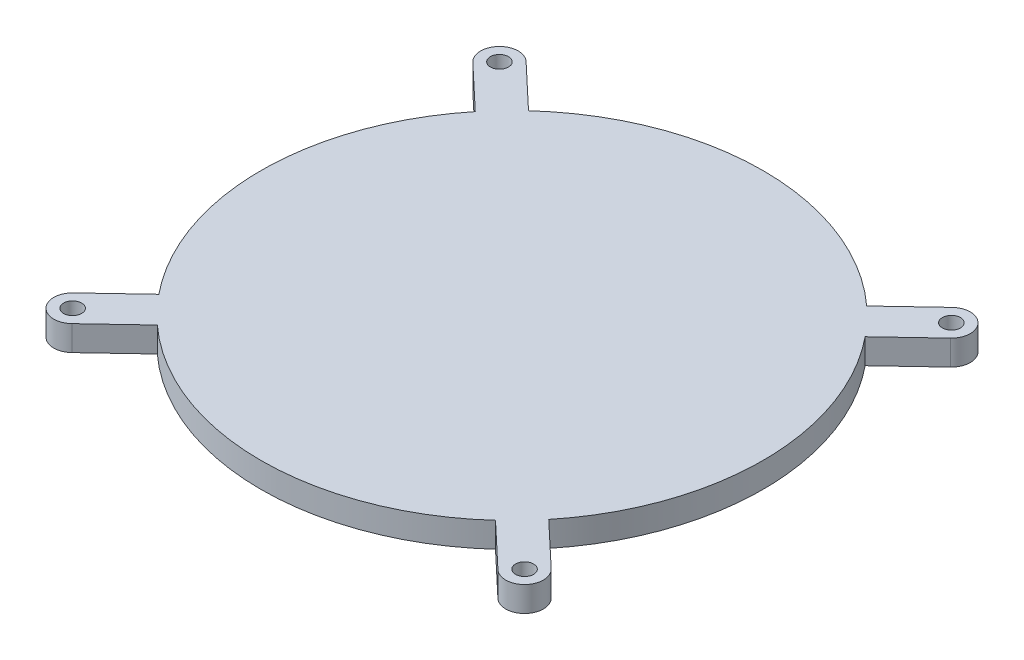
SolidWorks part; units mm, degrees
ref_plane "Plan de face" through (0, 0, 0) normal (0, 0, 1) x (1, 0, 0)
ref_plane "Plan de dessus" through (0, 0, 0) normal (0, 1, 0) x (1, 0, 0)
ref_plane "Plan de droite" through (0, 0, 0) normal (1, 0, 0) x (0, 0, -1)
sketch "Esquisse1" plane through (0, 0, 0) normal (0, 1, 0) x (1, 0, 0)
  line L0 (-45, 42.5) -> (45, -42.5) construction
  line L1 (45, 42.5) -> (-45, -42.5) construction
  line L2 (-47.5748, 39.7737) -> (-38.8231, 31.5082)
  line L3 (-42.4252, 45.2263) -> (-33.6734, 36.9608)
  line L4 (42.4252, 45.2263) -> (33.6734, 36.9608)
  line L5 (47.5748, 39.7737) -> (38.8231, 31.5082)
  line L6 (47.5748, -39.7737) -> (38.8231, -31.5082)
  line L7 (42.4252, -45.2263) -> (33.6734, -36.9608)
  line L8 (-42.4252, -45.2263) -> (-33.6734, -36.9608)
  line L9 (-47.5748, -39.7737) -> (-38.8231, -31.5082)
  arc A0 (-42.4252, 45.2263) -> (-47.5748, 39.7737) centre (-45, 42.5) ccw
  arc A1 (47.5748, 39.7737) -> (42.4252, 45.2263) centre (45, 42.5) ccw
  arc A2 (-47.5748, -39.7737) -> (-42.4252, -45.2263) centre (-45, -42.5) ccw
  arc A3 (42.4252, -45.2263) -> (47.5748, -39.7737) centre (45, -42.5) ccw
  arc A4 (-38.8231, 31.5082) -> (-38.8231, -31.5082) centre (0, 0) ccw
  arc A5 (33.6734, 36.9608) -> (-33.6734, 36.9608) centre (0, 0) ccw
  arc A6 (38.8231, -31.5082) -> (38.8231, 31.5082) centre (0, 0) ccw
  arc A7 (-33.6734, -36.9608) -> (33.6734, -36.9608) centre (0, 0) ccw
  point P8 (0, 0)
  point P26 (0, 0)
  point P27 (0, 0)
  point P28 (0, 0)
  point P29 (0, 0)
  dimension "D3" = 7.5
  dimension "D4" = 100
  dimension "D1" = 90
  dimension "D2" = 85
extrude "Boss.-Extru.1" add sketch "Esquisse1" along normal blind 5
hole_wizard "Dégagement M31" positions "Esquisse3D1" profile "Esquisse2" hole size "M3" standard "Ansi Metric" end condition through all
sketch3d "Esquisse3D1"
  line L0 (-45, 5, 42.5) -> (-45, 0, 42.5) construction
  line L1 (-45, 5, -42.5) -> (-45, 0, -42.5) construction
  line L2 (45, 5, -42.5) -> (45, 0, -42.5) construction
  line L3 (45, 5, 42.5) -> (45, 0, 42.5) construction
  point P0 (-45, 5, 42.5)
  point P4 (-45, 5, -42.5)
  point P8 (45, 5, -42.5)
  point P12 (45, 5, 42.5)
sketch "Esquisse2" plane through (-45, 5, 42.5) normal (1, 0, 0) x (0, 0, 1)
  line L0 (0, 0) -> (0, 5)
  line L1 (0, 5) -> (1.8, 5)
  line L2 (1.8, 5) -> (1.8, 0)
  line L5 (1.8, 0) -> (0, 0)
  line L11 (0, -6.35) -> (0, 107.95) construction
  dimension "Diamètre du perçage jusqu'au prochain" = 3.6
  dimension "Profondeur du perçage jusqu'au prochain" = 5
sketch "Esquisse3" plane through (0, 0, 0) normal (0, -1, 0) x (1, 0, 0)
  line L0 (-38.8231, 31.5082) -> (-33.6734, 36.9608)
  line L1 (-33.6734, 36.9608) -> (-42.4252, 45.2263)
  line L2 (-47.5748, 39.7737) -> (-38.8231, 31.5082)
  line L3 (38.8231, 31.5082) -> (47.5748, 39.7737)
  line L4 (42.4252, 45.2263) -> (33.6734, 36.9608)
  line L5 (33.6734, 36.9608) -> (42.4252, 45.2263) construction
  line L6 (33.6734, 36.9608) -> (38.8231, 31.5082)
  line L7 (38.8231, -31.5082) -> (33.6734, -36.9608)
  line L8 (33.6734, -36.9608) -> (42.4252, -45.2263)
  line L9 (47.5748, -39.7737) -> (38.8231, -31.5082)
  line L10 (-33.6734, -36.9608) -> (-38.8231, -31.5082)
  line L11 (-38.8231, -31.5082) -> (-47.5748, -39.7737)
  line L12 (-33.6734, -36.9608) -> (-42.4252, -45.2263)
  arc A0 (-42.4252, 45.2263) -> (-47.5748, 39.7737) centre (-45, 42.5) ccw
  arc A1 (47.5748, 39.7737) -> (42.4252, 45.2263) centre (45, 42.5) ccw
  arc A2 (33.6734, 36.9608) -> (-33.6734, 36.9608) centre (0, 0) ccw construction
  arc A3 (42.4252, -45.2263) -> (47.5748, -39.7737) centre (45, -42.5) ccw
  arc A5 (-42.4252, -45.2263) -> (-47.5748, -39.7737) centre (-45, -42.5) cw
